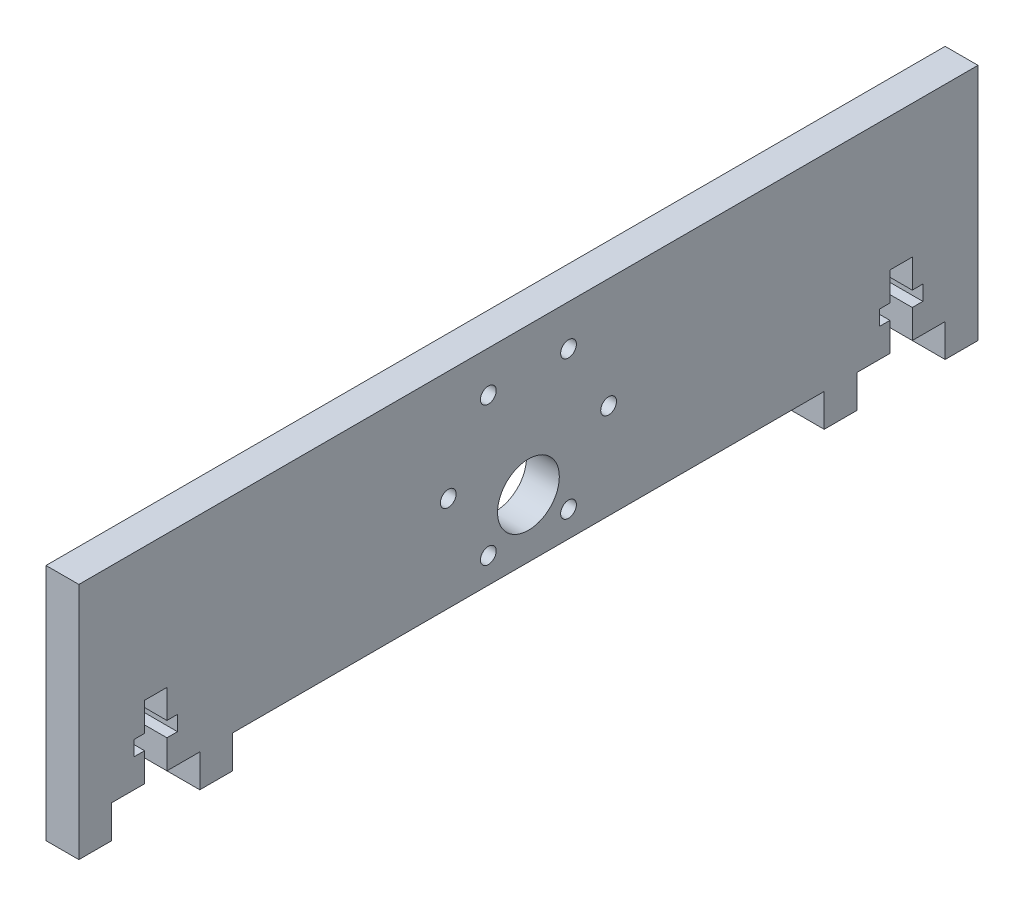
SolidWorks part; units mm, degrees
ref_plane "Front Plane" through (0, 0, 0) normal (0, 0, 1) x (1, 0, 0)
ref_plane "Top Plane" through (0, 0, 0) normal (0, 1, 0) x (1, 0, 0)
ref_plane "Right Plane" through (0, 0, 0) normal (1, 0, 0) x (0, 0, -1)
sketch "Motor plate" plane through (0, 0, 0) normal (1, 0, 0) x (0, 0, -1)
  line L0 (0, -1.4386) -> (7.747, 11.9796) construction
  line L1 (57.15, -19.8536) -> (-57.15, -19.8536)
  line L2 (57.15, -19.8536) -> (57.15, 19.8536) construction
  line L3 (57.15, 19.8536) -> (-57.15, 19.8536)
  line L4 (-57.15, -19.8536) -> (-57.15, 19.8536) construction
  line L5 (57.15, -19.8536) -> (-57.15, 19.8536) construction
  line L6 (57.15, 19.8536) -> (-57.15, -19.8536) construction
  line L7 (86.868, 19.8536) -> (57.15, 19.8536)
  line L8 (86.868, -19.8536) -> (86.868, 19.8536)
  line L9 (-86.868, -26.2036) -> (86.868, -26.2036) construction
  line L13 (0, 19.8536) -> (0, -19.8536) construction
  line L21 (-86.868, -19.8536) -> (-86.868, 19.8536)
  line L22 (-86.868, 19.8536) -> (-57.15, 19.8536)
  circle A0 centre (7.747, 11.9796) radius 1.524
  circle A1 centre (15.494, -1.4386) radius 1.524
  circle A2 centre (7.747, -14.8568) radius 1.524
  circle A3 centre (-7.747, -14.8568) radius 1.524
  circle A4 centre (-15.494, -1.4386) radius 1.524
  circle A5 centre (-7.747, 11.9796) radius 1.524
  circle A6 centre (0, -8.5506) radius 5.969
  circle A7 centre (0, -1.4386) radius 18.415 construction
  point P0 (0, 0)
  point P15 (0, -1.4386)
  point P32 (0, -1.4386)
  line B0 (-80.518, -19.8536) -> (-80.518, -26.2036)
  line B1 (-80.518, -26.2036) -> (-86.868, -26.2036)
  line B2 (-86.868, -26.2036) -> (-86.868, -19.8536)
  line B3 (-74.168, -19.8536) -> (-74.168, -14.3186)
  line B4 (-74.168, -14.3186) -> (-76.209, -14.3186)
  line B5 (-76.209, -14.3186) -> (-76.209, -11.4186)
  line B6 (-76.209, -11.4186) -> (-74.168, -11.4186)
  line B7 (-74.168, -11.4186) -> (-74.168, -5.8836)
  line B8 (-74.168, -5.8836) -> (-69.85, -5.8836)
  line B9 (-69.85, -5.8836) -> (-69.85, -11.4186)
  line B10 (-69.85, -11.4186) -> (-67.809, -11.4186)
  line B11 (-67.809, -11.4186) -> (-67.809, -14.3186)
  line B12 (-67.809, -14.3186) -> (-69.85, -14.3186)
  line B13 (-69.85, -14.3186) -> (-69.85, -19.8536)
  line B14 (-72.009, -5.8836) -> (-72.009, -19.8536) construction
  line B15 (-63.5, -19.8536) -> (-69.85, -19.8536)
  line B16 (-57.15, -26.2036) -> (-57.15, -19.8536)
  line B17 (-80.518, -19.8536) -> (-74.168, -19.8536)
  line B18 (-63.5, -26.2036) -> (-57.15, -26.2036)
  line B19 (-63.5, -19.8536) -> (-63.5, -26.2036)
  line B20 (80.518, -19.8536) -> (80.518, -26.2036)
  line B21 (80.518, -26.2036) -> (86.868, -26.2036)
  line B22 (86.868, -26.2036) -> (86.868, -19.8536)
  line B23 (74.168, -19.8536) -> (74.168, -14.3186)
  line B24 (74.168, -14.3186) -> (76.209, -14.3186)
  line B25 (76.209, -14.3186) -> (76.209, -11.4186)
  line B26 (76.209, -11.4186) -> (74.168, -11.4186)
  line B27 (74.168, -11.4186) -> (74.168, -5.8836)
  line B28 (74.168, -5.8836) -> (69.85, -5.8836)
  line B29 (69.85, -5.8836) -> (69.85, -11.4186)
  line B30 (69.85, -11.4186) -> (67.809, -11.4186)
  line B31 (67.809, -11.4186) -> (67.809, -14.3186)
  line B32 (67.809, -14.3186) -> (69.85, -14.3186)
  line B33 (69.85, -14.3186) -> (69.85, -19.8536)
  line B34 (72.009, -5.8836) -> (72.009, -19.8536) construction
  line B35 (63.5, -19.8536) -> (69.85, -19.8536)
  line B36 (57.15, -26.2036) -> (57.15, -19.8536)
  line B37 (80.518, -19.8536) -> (74.168, -19.8536)
  line B38 (63.5, -26.2036) -> (57.15, -26.2036)
  line B39 (63.5, -19.8536) -> (63.5, -26.2036)
  dimension "D3" = 30
  dimension "D4" = 15.494
  dimension "D5" = 3.048
  dimension "D8" = 11.938
  dimension "D2" = 36.83
  dimension "D1" = 114.3
  dimension "D6" = 6.35
  dimension "D7" = 6
  dimension "D9" = 7.112
sketch_block_instance "Male T-slot assembly-3"
sketch_block "Male T-slot assembly" parameters "D1"=6.35, "D2"=6.35, "D3"=4.318, "D4"=2.9, "D5"=8.4, "D6"=13.97, "D7"=6.35
sketch_block_instance "Male T-slot assembly-5"
extrude "Boss-Extrude1" add sketch "Motor plate" along normal blind 6.35 contours B39 B35 B33 B32 B31 B30 B29 B28 B27 B26 B25 B24 B23 B37 B20 B21 B22 L8 L7 L3 L22 L21 B2 B1 B0 B17 B3 B4 B5 B6 B7 B8 B9 B10 B11 B12 B13 B15 B19 B18 B16 L1 B36 B38
equation "\"D1@Motor plate\"=\"Wheel Diameter\" + 2 * \"Sheet Thickness\""
equation "\"Ball Diameter\"= 1.75in"
equation "\"Sheet Thickness\"= 0.25in"
equation "\"Screw Diameter\"= .17in"
equation "\"Robot Diameter\"= 14in"
equation "\"Castor Screw Diameter\"= 0.22in"
equation "\"Wheel Diameter\" = 4in"
equation "\"Nut Diameter\" = 8.4mm"
equation "\"Nut Height\" = 2.9mm"
equation "\"Screw Height\" = 0.55in"
equation "\"D1@Boss-Extrude1\"=\"Sheet Thickness\""
equation "\"D3@Motor plate\"=360/12deg"
equation "\"Ball Radius\" = \"Ball Diameter\"/2"
equation "\"Pulley Diameter\" = 1in"
equation "\"Reactor Height\" = 14in"
equation "\"Elevator Height\" = 11.5in"
equation "\"Elevator Width\" = \"Ball Diameter\" + 0.25in"
equation "\"Elevator Bearing Diameter\" = sqr(2*(\"Sheet Thickness\"^2)) + 0.2in"
equation "\"Elevator Axle Endcap Diameter\" = \"Pulley Diameter\" + 0.25in"
equation "\"Elevator Axle Length\" = \"Elevator Width\" + 8*\"Sheet Thickness\""
equation "\"Elevator Clearance from Axis\" = 3.28in"
equation "\"Elevator Horizontal Clearance\" = \"Elevator Width\" + 0.5in"
equation "\"Claw Horizontal Seperation\" = (\"Elevator Width\"/2) - (1.5 * \"Sheet Thickness\") - 0.15in"
equation "\"Claw Radius\" = \"Ball Radius\" + 0.1in"
equation "\"Castor Wheel Height\" = 1.25in"
